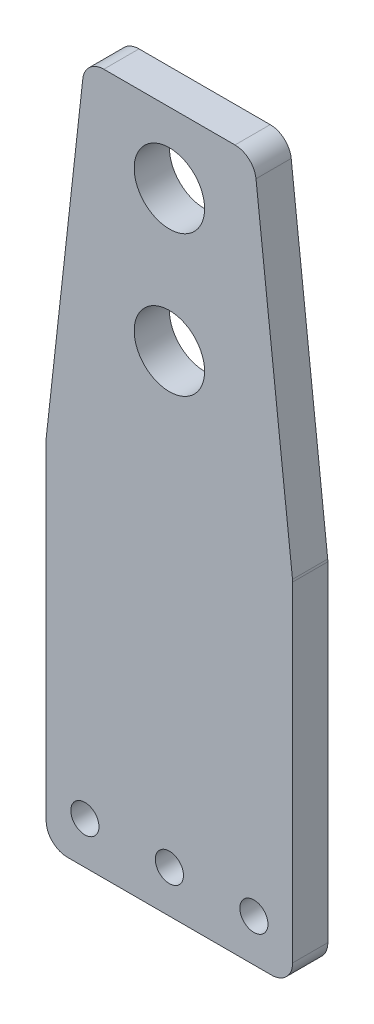
SolidWorks part; units mm, degrees
ref_plane "前视基准面" through (0, 0, 0) normal (0, 0, 1) x (1, 0, 0)
ref_plane "上视基准面" through (0, 0, 0) normal (0, 1, 0) x (1, 0, 0)
ref_plane "右视基准面" through (0, 0, 0) normal (1, 0, 0) x (0, 0, -1)
sketch "草图1" plane through (0, 0, 0) normal (0, 0, 1) x (1, 0, 0)
  line L0 (-35, 0) -> (0, 0)
  line L1 (0, 0) -> (0, 50)
  line L2 (0, 50) -> (-5.5, 99.5)
  line L3 (-5.5, 99.5) -> (-29.5, 99.5)
  line L4 (-29.5, 99.5) -> (-35, 50)
  line L5 (-35, 50) -> (-35, 0)
  dimension "D1" = 99.5
  dimension "D2" = 35
  dimension "D3" = 24
  dimension "D4" = 50
extrude "凸台-拉伸1" add sketch "草图1" along normal blind 5
fillet "圆角1" radius 3 6 edges at (0, 0, 2.5) (-35, 0, 2.5) (0, 50, 2.5) (-5.5, 99.5, 2.5) (-35, 50, 2.5) (-29.5, 99.5, 2.5)
sketch "草图2" plane through (0, 0, 5) normal (0, 0, 1) x (1, 0, 0)
  line L0 (-32, 0) -> (-3, 0) construction
  line L1 (-8.1851, 99.5) -> (-26.8149, 99.5) construction
  line L2 (0, 3) -> (0, 49.8338) construction
  circle A0 centre (-29.5, 6) radius 2
  circle A1 centre (-17.5, 6) radius 2
  circle A2 centre (-5.5, 6) radius 2
  circle A5 centre (-17.5, 89.5) radius 4.5
  circle A6 centre (-17.5, 69.5) radius 4.5
  dimension "D2" = 4
  dimension "D6" = 9
  dimension "D3" = 5.5
  dimension "D4" = 24
  dimension "D5" = 6
  dimension "D7" = 10
  dimension "D8" = 17.5
  dimension "D9" = 20
  dimension "D1" = 3
extrude "切除-拉伸1" cut sketch "草图2" against normal through all
hole_wizard "M10 螺纹孔5" positions "草图8" profile "草图9" tap size "M10" standard "GB"
sketch "草图8" plane through (0, 0, 5) normal (0, 0, 1) x (1, 0, 0)
  point P0 (-17.5, 69.5)
  point P3 (-17.5, 89.5)
sketch "草图9" plane through (-17.5, 69.5, 5) normal (1, 0, 0) x (0, -1, 0)
  line L0 (0, 0) -> (0, 24.5)
  line L1 (0, 24.5) -> (5, 24.5)
  line L2 (5, 24.5) -> (5, 0)
  line L5 (5, 0) -> (0, 0)
  line L10 (0, 24.5) -> (-5, 24.5) construction
  line L11 (0, -6.35) -> (0, 107.95) construction
  dimension "螺纹孔钻头直径" = 10
  dimension "螺纹孔钻头深度" = 24.5
  dimension "导头角度" = 180
cosmetic thread "孔螺蚊线3"
cosmetic thread "孔螺蚊线4"
